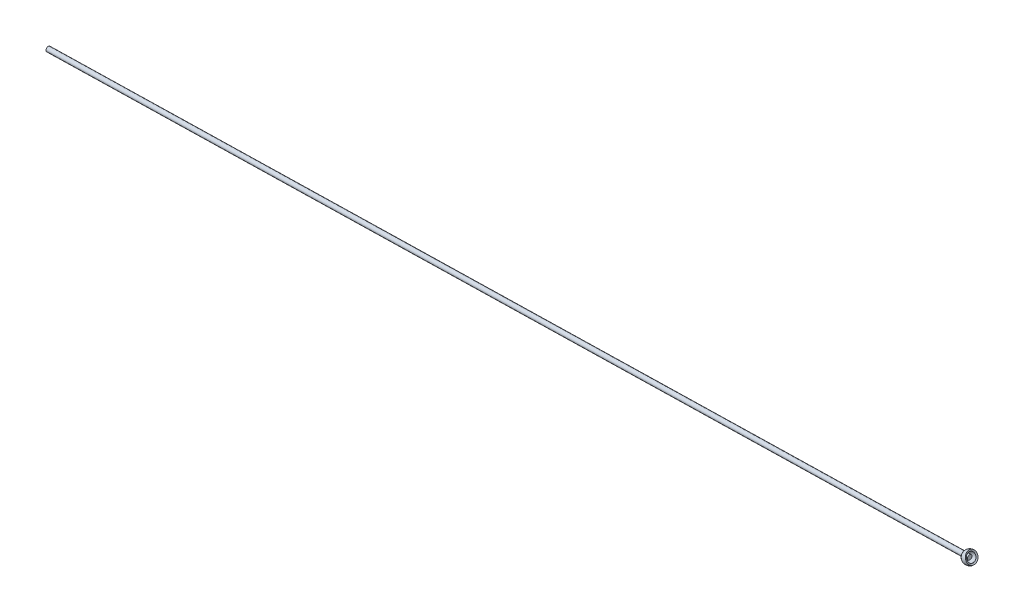
SolidWorks part; units mm, degrees
ref_plane "Plan de face" through (0, 0, 0) normal (0, 0, 1) x (1, 0, 0)
ref_plane "Plan de dessus" through (0, 0, 0) normal (0, 1, 0) x (1, 0, 0)
ref_plane "Plan de droite" through (0, 0, 0) normal (1, 0, 0) x (0, 0, -1)
sketch "Esquisse2" plane through (0, 0, 0) normal (0, 0, 1) x (1, 0, 0)
  line L0 (-291.1616, -154.3318) -> (-891.0121, -167.7232)
  line L1 (-993, -170) -> (-291.1616, -154.3318) construction
  dimension "D1" = 600
sketch "Esquisse3" plane through (0, 0, 0) normal (0, 0, 1) x (1, 0, 0)
  line L0 (-891.0121, -167.7232) -> (-291.1616, -154.3318)
ref_plane "Plan1" through (-291.1616, -154.3318, 0) normal (0.9998, 0.0223, 0) x (0, 0, -1)
sketch "Esquisse4" plane through (-291.1616, -154.3318, 0) normal (0.9998, 0.0223, 0) x (0, 0, -1)
  circle A0 centre (0, 0) radius 1.5
  dimension "D1" = 3
extrude "Boss.-Extru.1" add sketch "Esquisse4" against normal up to vertex (600 mm away) up to point (-891.0121, -167.7232, 0)
sketch "Esquisse5" plane through (0, 0, 0) normal (0, 0, 1) x (1, 0, 0)
  line L0 (-293.8405, -155.6821) -> (-288.4827, -152.9815) construction
  line L4 (-291.5142, -151.3526) -> (-291.1616, -154.3318) construction
  line L6 (-291.1616, -154.3318) -> (-97.4173, -164.2892) construction
  arc A0 (-291.5142, -151.3526) -> (-293.8405, -155.6821) centre (-291.1616, -154.3318) ccw
  arc A2 (-288.1655, -154.4858) -> (-294.1576, -154.1778) centre (-291.1616, -154.3318) ccw construction
  arc A3 (-288.4899, -152.9671) -> (-288.6439, -155.9632) centre (-291.1616, -154.3318) ccw construction
  dimension "D1" = 70
  dimension "D2" = 29.693
revolve "Révol.-Mince1" add sketch "Esquisse5" angle 360 about L0
